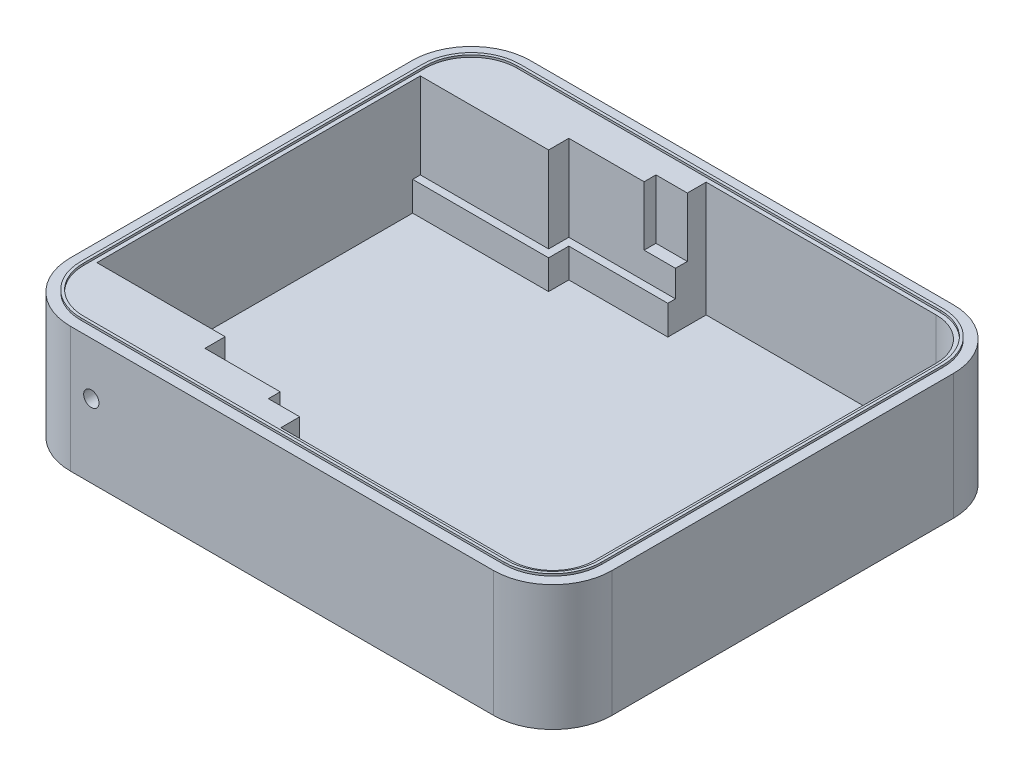
SolidWorks part; units mm, degrees
ref_plane "Front Plane" through (0, 0, 0) normal (0, 0, 1) x (1, 0, 0)
ref_plane "Top Plane" through (0, 0, 0) normal (0, 1, 0) x (1, 0, 0)
ref_plane "Right Plane" through (0, 0, 0) normal (1, 0, 0) x (0, 0, -1)
sketch "Sketch1" plane through (0, 0, 0) normal (0, 1, 0) x (1, 0, 0)
  line L1 (-36.35, -30.5) -> (36.35, -30.5)
  line L2 (-36.35, -30.5) -> (-36.35, 30.5)
  line L3 (-36.35, 30.5) -> (36.35, 30.5)
  line L4 (36.35, -30.5) -> (36.35, 30.5)
  line L5 (-36.35, -30.5) -> (36.35, 30.5) construction
  line L6 (-36.35, 30.5) -> (36.35, -30.5) construction
  point P0 (0, 0)
  dimension "D1" = 61
  dimension "D2" = 72.7
extrude "Boss-Extrude1" add sketch "Sketch1" along normal blind 1.5
sketch "Sketch3" plane through (0, 0, 0) normal (0, -1, 0) x (1, 0, 0)
  line L8 (38.35, -32.5) -> (38.35, 32.5)
  line L9 (38.35, 32.5) -> (-38.35, 32.5)
  line L10 (-38.35, 32.5) -> (-38.35, -32.5)
  line L11 (-38.35, -32.5) -> (38.35, -32.5)
  line L12 (38.35, -32.5) -> (38.35, 32.5)
  line L13 (38.35, 32.5) -> (-38.35, 32.5)
  line L14 (-38.35, 32.5) -> (-38.35, -32.5)
  line L15 (-38.35, -32.5) -> (38.35, -32.5)
  dimension "D2" = 32.5
  dimension "D1" = 2
extrude "Boss-Extrude5" add sketch "Sketch3" against normal blind 1.5
sketch "Sketch2" plane through (0, 1.5, 0) normal (0, 1, 0) x (1, 0, 0)
  line L1 (-36.35, -22.1) -> (-17.95, -22.1)
  line L2 (-36.35, -22.1) -> (-36.35, 22.1)
  line L3 (-36.35, 22.1) -> (-17.95, 22.1)
  line L4 (-17.95, 22.1) -> (-17.95, 26.1)
  line L5 (-0.825, 0) -> (0.825, 0) construction
  line L6 (-36.35, 0) -> (36.1116, 0) construction
  line L7 (-2.65, -30.5) -> (36.35, -30.5)
  line L8 (-17.95, -26.1) -> (-3.85, -26.1)
  line L9 (-17.95, -26.1) -> (-17.95, -22.1)
  line L10 (-17.95, 26.1) -> (-3.85, 26.1)
  line L11 (-3.85, -26.1) -> (-3.85, -22.1)
  line L12 (36.35, 30.5) -> (-2.65, 30.5)
  line L13 (-3.85, 26.1) -> (-3.85, 22.1)
  line L14 (-3.85, 22.1) -> (-2.65, 22.1)
  line L15 (-2.65, 26.1) -> (-2.65, 22.1)
  line L16 (-2.65, -26.1) -> (-2.65, -22.1)
  line L17 (-3.85, -22.1) -> (-2.65, -22.1)
  line L18 (36.35, -30.5) -> (36.35, 30.5)
  line L19 (38.35, 32.5) -> (-38.35, 32.5)
  line L20 (38.35, 32.5) -> (38.35, -32.5)
  line L21 (38.35, -32.5) -> (-38.35, -32.5)
  line L22 (-38.35, 32.5) -> (-38.35, -32.5)
  line L23 (-2.65, -26.1) -> (-2.65, -30.5)
  line L37 (-2.65, 30.5) -> (-2.65, 26.1)
  line L38 (-3.85, 22.1) -> (-3.85, 26.1)
  line M43 (38.35, 32.5) -> (-38.35, 32.5)
  line M44 (-38.35, 32.5) -> (-38.35, -32.5)
  line M45 (-38.35, -32.5) -> (38.35, -32.5)
  line M46 (38.35, -32.5) -> (38.35, 32.5)
  dimension "D1" = 18.4
  dimension "D2" = 44.2
  dimension "D3" = 22.1
  dimension "D4" = 14.1
  dimension "D6" = 1.2
  dimension "D7" = 4
  dimension "D8" = 52.2
  dimension "D9" = 1.2
  dimension "D10" = 14.1
  dimension "D11" = 15.3
  dimension "D12" = 4
extrude "Boss-Extrude6" add sketch "Sketch2" along normal blind 4.2 contours L37 L12 L18 L7 L23 L16 L17 L11 L8 L9 L1 L2 L3 L4 L10 L13 L14 L15 M46 M43 M44 M45
sketch "Sketch4" plane through (0, 5.7, 0) normal (0, 1, 0) x (1, 0, 0)
  line L0 (-17.95, -26.1) -> (-17.95, -22.1) construction
  line L2 (-36.35, -22.1) -> (-36.35, -23.2)
  line L3 (-36.35, -23.2) -> (-17.95, -23.2)
  line L4 (38.35, -32.5) -> (38.35, 32.5)
  line L5 (38.35, 32.5) -> (-38.35, 32.5)
  line L6 (-38.35, 32.5) -> (-38.35, -32.5)
  line L7 (-38.35, -32.5) -> (38.35, -32.5)
  line L8 (38.35, -32.5) -> (38.35, 32.5)
  line L9 (38.35, 32.5) -> (-38.35, 32.5)
  line L10 (-38.35, 32.5) -> (-38.35, -32.5)
  line L11 (-38.35, -32.5) -> (38.35, -32.5)
  line L13 (-17.95, 22.1) -> (-17.95, 26.1) construction
  line L15 (-36.35, 22.1) -> (-36.35, 23.2)
  line L16 (-36.35, 23.2) -> (-17.95, 23.2)
  line L18 (-36.35, -22.1) -> (-36.35, 22.1)
  line L19 (-17.95, 23.2) -> (-17.95, 26.1)
  line L20 (-17.95, 26.1) -> (-3.85, 26.1)
  line L21 (-3.85, 26.1) -> (-3.85, 22.1)
  line L22 (-3.85, 22.1) -> (-2.65, 22.1)
  line L23 (-2.65, 22.1) -> (-2.65, 30.5)
  line L24 (-2.65, 30.5) -> (36.35, 30.5)
  line L25 (36.35, 30.5) -> (36.35, -30.5)
  line L26 (36.35, -30.5) -> (-2.65, -30.5)
  line L27 (-2.65, -30.5) -> (-2.65, -22.1)
  line L28 (-2.65, -22.1) -> (-3.85, -22.1)
  line L29 (-3.85, -22.1) -> (-3.85, -26.1)
  line L30 (-3.85, -26.1) -> (-17.95, -26.1)
  line L31 (-17.95, -26.1) -> (-17.95, -23.2)
  dimension "D1" = 0
extrude "Boss-Extrude7" add sketch "Sketch4" along normal blind 3.8
sketch "Sketch5" plane through (0, 9.5, 0) normal (0, 1, 0) x (1, 0, 0)
  line L0 (-17.95, -26.1) -> (-3.85, -26.1) construction
  line L3 (-2.65, -27.8) -> (-3.85, -27.8)
  line L4 (-38.35, -32.5) -> (38.35, -32.5)
  line L5 (38.35, -32.5) -> (38.35, 32.5)
  line L6 (38.35, 32.5) -> (-38.35, 32.5)
  line L7 (-38.35, 32.5) -> (-38.35, -32.5)
  line L8 (-38.35, -32.5) -> (38.35, -32.5)
  line L9 (38.35, -32.5) -> (38.35, 32.5)
  line L10 (38.35, 32.5) -> (-38.35, 32.5)
  line L11 (-38.35, 32.5) -> (-38.35, -32.5)
  line L13 (-3.85, -27.8) -> (-7.15, -27.8)
  line L16 (-7.15, -27.8) -> (-7.15, -26.1)
  line L17 (-2.65, 30.5) -> (-2.65, 22.1) construction
  line L20 (-3.85, 27.8) -> (-2.65, 27.8)
  line L22 (-3.85, 26.1) -> (-17.95, 26.1) construction
  line L23 (-3.85, 27.8) -> (-7.15, 27.8)
  line L26 (-7.15, 27.8) -> (-7.15, 26.1)
  line L27 (-7.15, -26.1) -> (-17.95, -26.1)
  line L28 (-17.95, -26.1) -> (-17.95, -23.2)
  line L29 (-17.95, -23.2) -> (-36.35, -23.2)
  line L30 (-36.35, -23.2) -> (-36.35, 23.2)
  line L31 (-36.35, 23.2) -> (-17.95, 23.2)
  line L32 (-17.95, 23.2) -> (-17.95, 26.1)
  line L33 (-17.95, 26.1) -> (-7.15, 26.1)
  line L34 (-2.65, 27.8) -> (-2.65, 30.5)
  line L35 (-2.65, 30.5) -> (36.35, 30.5)
  line L36 (36.35, 30.5) -> (36.35, -30.5)
  line L37 (36.35, -30.5) -> (-2.65, -30.5)
  line L38 (-2.65, -30.5) -> (-2.65, -27.8)
  dimension "D2" = 1.2
  dimension "D4" = 3.3
  dimension "D1" = 0
extrude "Boss-Extrude8" add sketch "Sketch5" along normal blind 8.5
sketch "Sketch7" plane through (0, 0, 23.2) normal (0, 0, -1) x (-1, 0, 0)
  line L0 (36.35, 18) -> (36.35, 5.7) construction
  line L1 (36.35, 18) -> (17.95, 18) construction
  circle A0 centre (27.35, 10.5) radius 1.1
  dimension "D1" = 2.2
  dimension "D2" = 9
  dimension "D3" = 7.5
extrude "Cut-Extrude1" cut sketch "Sketch7" against normal blind 20.8
fillet "Fillet3" radius 8 2 edges at (-38.35, 9, -32.5) (-38.35, 9, 32.5)
sketch "Sketch9" plane through (0, 9.5, 0) normal (0, 1, 0) x (1, 0, 0)
  line L1 (-2.65, 22.1) -> (-3.85, 22.1)
  line L2 (-2.65, 22.1) -> (-2.65, 26.1)
  line L3 (-2.65, 26.1) -> (-3.85, 26.1)
  line L4 (-3.85, 22.1) -> (-3.85, 26.1)
  line L5 (-2.65, -22.1) -> (-3.85, -22.1)
  line L6 (-2.65, -22.1) -> (-2.65, -26.1)
  line L7 (-2.65, -26.1) -> (-3.85, -26.1)
  line L8 (-3.85, -22.1) -> (-3.85, -26.1)
extrude "Cut-Extrude2" cut sketch "Sketch9" against normal up to surface (8 mm away) up to face at (-6.1125, 1.5, 0)
sketch "Sketch11" plane through (0, 1.5, 0) normal (0, 1, 0) x (1, 0, 0)
  line L0 (-17.95, -26.1) -> (-2.65, -26.1) construction
  line L1 (-17.95, -22.1) -> (-16.85, -22.1)
  line L2 (-17.95, -22.1) -> (-17.95, -26.1)
  line L3 (-17.95, -26.1) -> (-16.85, -26.1)
  line L4 (-16.85, -22.1) -> (-16.85, -26.1)
  line L6 (-17.95, 26.1) -> (-2.65, 26.1) construction
  line L7 (-2.65, -26.1) -> (-17.95, -26.1)
  line L8 (-2.65, -26.1) -> (-2.65, -25)
  line L9 (-2.65, -25) -> (-17.95, -25)
  line L10 (-17.95, -26.1) -> (-17.95, -25)
  line L11 (-17.95, 22.1) -> (-16.85, 22.1)
  line L12 (-17.95, 22.1) -> (-17.95, 26.1)
  line L13 (-17.95, 26.1) -> (-16.85, 26.1)
  line L14 (-16.85, 22.1) -> (-16.85, 26.1)
  line L16 (-2.65, 26.1) -> (-16.85, 26.1)
  line L17 (-2.65, 26.1) -> (-2.65, 25)
  line L18 (-2.65, 25) -> (-16.85, 25)
  line L19 (-16.85, 26.1) -> (-16.85, 25)
  line M9 (-2.65, 26.1) -> (-17.95, 26.1)
  line M10 (-17.95, 26.1) -> (-17.95, 22.1)
  line M14 (-17.95, -22.1) -> (-17.95, -26.1)
  dimension "D1" = 1.1
  dimension "D2" = 1.1
  dimension "D3" = 1.1
  dimension "D4" = 1.1
extrude "Boss-Extrude11" add sketch "Sketch11" along normal blind 4.2 contours L11 L14 M9 M10 | L18 L17 L14 M9 | L9 L4 L1 M14
fillet "Fillet4" radius 6 2 edges at (36.35, 9.75, -30.5) (36.35, 9.75, 30.5)
fillet "Fillet2" radius 8 2 edges at (38.35, 9, -32.5) (38.35, 9, 32.5)
sketch "Sketch12" plane through (0, 18, 0) normal (0, 1, 0) x (1, 0, 0)
  line L0 (-30.35, -33) -> (30.35, -33)
  line L1 (38.85, -24.5) -> (38.85, 24.5)
  line L2 (30.35, 33) -> (-30.35, 33)
  line L3 (-38.85, 24.5) -> (-38.85, -24.5)
  line L4 (38.35, -24.5) -> (38.35, 24.5)
  line L5 (30.35, 32.5) -> (-30.35, 32.5)
  line L6 (-38.35, 24.5) -> (-38.35, -24.5)
  line L7 (-30.35, -32.5) -> (30.35, -32.5)
  line L8 (38.35, -24.5) -> (38.35, 24.5)
  line L9 (30.35, 32.5) -> (-30.35, 32.5)
  line L10 (-38.35, 24.5) -> (-38.35, -24.5)
  line L11 (-30.35, -32.5) -> (30.35, -32.5)
  arc A0 (30.35, -33) -> (38.85, -24.5) centre (30.35, -24.5) ccw
  arc A1 (38.85, 24.5) -> (30.35, 33) centre (30.35, 24.5) ccw
  arc A2 (-30.35, 33) -> (-38.85, 24.5) centre (-30.35, 24.5) ccw
  arc A3 (-38.85, -24.5) -> (-30.35, -33) centre (-30.35, -24.5) ccw
  arc A4 (38.35, 24.5) -> (30.35, 32.5) centre (30.35, 24.5) ccw
  arc A5 (-30.35, 32.5) -> (-38.35, 24.5) centre (-30.35, 24.5) ccw
  arc A6 (-38.35, -24.5) -> (-30.35, -32.5) centre (-30.35, -24.5) ccw
  arc A7 (30.35, -32.5) -> (38.35, -24.5) centre (30.35, -24.5) ccw
  arc A8 (38.35, 24.5) -> (30.35, 32.5) centre (30.35, 24.5) ccw
  arc A9 (-30.35, 32.5) -> (-38.35, 24.5) centre (-30.35, 24.5) ccw
  arc A10 (-38.35, -24.5) -> (-30.35, -32.5) centre (-30.35, -24.5) ccw
  arc A11 (30.35, -32.5) -> (38.35, -24.5) centre (30.35, -24.5) ccw
  dimension "D1" = 0
  dimension "D2" = 0.5
extrude "Boss-Extrude12" add sketch "Sketch12" against normal up to surface (18 mm away) up to face at (0, 0, 0)
sketch "Sketch13" plane through (0, 18, 0) normal (0, 1, 0) x (1, 0, 0)
  line L4 (-36.95, 24.5) -> (-36.95, -24.5)
  line L5 (-30.35, -31.1) -> (30.35, -31.1)
  line L6 (36.95, -24.5) -> (36.95, 24.5)
  line L7 (30.35, 31.1) -> (-30.35, 31.1)
  line L8 (-30.35, -31.5) -> (30.35, -31.5)
  line L9 (37.35, -24.5) -> (37.35, 24.5)
  line L10 (30.35, 31.5) -> (-30.35, 31.5)
  line L11 (-37.35, 24.5) -> (-37.35, -24.5)
  line L12 (-30.35, -31.5) -> (30.35, -31.5)
  line L13 (37.35, -24.5) -> (37.35, 24.5)
  line L14 (30.35, 31.5) -> (-30.35, 31.5)
  line L15 (-37.35, 24.5) -> (-37.35, -24.5)
  arc A4 (-36.95, -24.5) -> (-30.35, -31.1) centre (-30.35, -24.5) ccw
  arc A5 (30.35, -31.1) -> (36.95, -24.5) centre (30.35, -24.5) ccw
  arc A6 (36.95, 24.5) -> (30.35, 31.1) centre (30.35, 24.5) ccw
  arc A7 (-30.35, 31.1) -> (-36.95, 24.5) centre (-30.35, 24.5) ccw
  arc A8 (-37.35, -24.5) -> (-30.35, -31.5) centre (-30.35, -24.5) ccw
  arc A9 (30.35, -31.5) -> (37.35, -24.5) centre (30.35, -24.5) ccw
  arc A10 (37.35, 24.5) -> (30.35, 31.5) centre (30.35, 24.5) ccw
  arc A11 (-30.35, 31.5) -> (-37.35, 24.5) centre (-30.35, 24.5) ccw
  arc A12 (-37.35, -24.5) -> (-30.35, -31.5) centre (-30.35, -24.5) ccw
  arc A13 (30.35, -31.5) -> (37.35, -24.5) centre (30.35, -24.5) ccw
  arc A14 (37.35, 24.5) -> (30.35, 31.5) centre (30.35, 24.5) ccw
  arc A15 (-30.35, 31.5) -> (-37.35, 24.5) centre (-30.35, 24.5) ccw
  dimension "D1" = 1.5
  dimension "D2" = 0.4
extrude "Boss-Extrude13" add sketch "Sketch13" along normal blind 0.3
sketch "Sketch14" plane through (0, 0, 23.2) normal (0, 0, -1) x (-1, 0, 0)
  circle A0 centre (27.35, 10.5) radius 1.1 construction
  circle A1 centre (27.35, 10.5) radius 1.1
extrude "Cut-Extrude3" cut sketch "Sketch14" against normal blind 14
